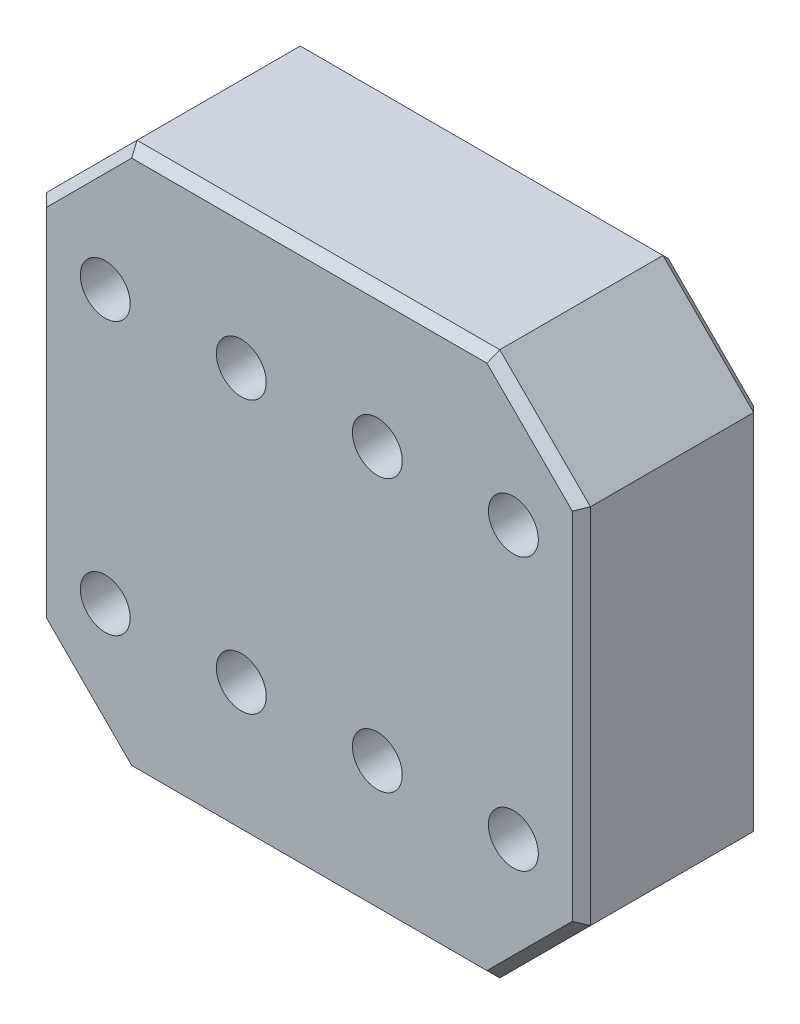
SolidWorks part; units mm, degrees
material "Q235-A"
ref_plane "前视基准面" through (0, 0, 0) normal (0, 0, 1) x (1, 0, 0)
ref_plane "上视基准面" through (0, 0, 0) normal (0, 1, 0) x (1, 0, 0)
ref_plane "右视基准面" through (0, 0, 0) normal (1, 0, 0) x (0, 0, -1)
sketch "草图1" plane through (0, 0, 0) normal (0, 0, 1) x (1, 0, 0)
  line L1 (-30, 30) -> (30, 30)
  line L2 (-30, 30) -> (-30, -30)
  line L3 (-30, -30) -> (30, -30)
  line L4 (30, 30) -> (30, -30)
  line L5 (-30, 30) -> (30, -30) construction
  line L6 (-30, -30) -> (30, 30) construction
  point P0 (0, 0)
  dimension "D1" = 60
  dimension "D2" = 60
extrude "凸台-拉伸1" add sketch "草图1" along normal blind 20
hole_wizard "打孔尺寸(%根据)内六角圆柱头螺钉的类型1" positions "草图5" profile "草图6" counterbore size "M5" standard "GB" end condition through all
sketch "草图5" plane through (0, 0, 0) normal (0, 0, -1) x (-1, 0, 0)
  line L7 (0, 0) -> (-15, 0) construction
  line L10 (-22.5, 15) -> (-7.5, 15) construction
  line L11 (-22.5, 15) -> (-22.5, -15) construction
  line L12 (-22.5, -15) -> (-7.5, -15) construction
  line L13 (-7.5, 15) -> (-7.5, -15) construction
  line L14 (-22.5, 15) -> (-7.5, -15) construction
  line L15 (-22.5, -15) -> (-7.5, 15) construction
  line L16 (0, 0) -> (15, 0) construction
  line L19 (7.5, 15) -> (22.5, 15) construction
  line L20 (7.5, 15) -> (7.5, -15) construction
  line L21 (7.5, -15) -> (22.5, -15) construction
  line L22 (22.5, 15) -> (22.5, -15) construction
  line L23 (7.5, 15) -> (22.5, -15) construction
  line L24 (7.5, -15) -> (22.5, 15) construction
  point P0 (-22.5, 15)
  point P2 (-22.5, -15)
  point P4 (-7.5, 15)
  point P6 (-7.5, -15)
  point P180 (-15, 0)
  point P191 (22.5, -15)
  point P380 (7.5, 15)
  point P381 (7.5, -15)
  point P382 (22.5, 15)
  point P385 (15, 0)
  dimension "D1" = 15
  dimension "D2" = 30
  dimension "D3" = 15
sketch "草图6" plane through (22.5, 15, 0) normal (1, 0, 0) x (0, 1, 0)
  line L0 (0, 0) -> (0, 20)
  line L1 (0, 20) -> (2.75, 20)
  line L3 (2.75, 20) -> (2.75, 14)
  line L4 (2.75, 14) -> (5, 14)
  line L5 (5, 14) -> (5, 0)
  line L7 (5, 0) -> (0, 0)
  line L11 (0, -6.35) -> (0, 107.95) construction
  dimension "通孔孔直径" = 5.5
  dimension "通孔孔深度" = 20
  dimension "柱形沉头孔直径" = 10
  dimension "柱形沉头孔深度" = 14
chamfer "倒角1" distance 10 angle 45 4 edges at (-30, -30, 10) (-30, 30, 10) (30, -30, 10) (30, 30, 10)
chamfer "倒角2" distance 1 angle 45 16 edges at (25, -25, 0) (25, 25, 0) (0, 30, 0) (-25, 25, 0) (-25, -25, 0) (0, -30, 0) (25, 25, 20) (30, 0, 20) (25, -25, 20) (0, -30, 20) (-25, -25, 20) (-30, 0, 20) (-25, 25, 20) (0, 30, 20) (30, 0, 0) (-30, 0, 0)
hole_wizard "M10 螺纹孔1" positions "草图9" profile "草图10" tap size "M10" standard "GB"
sketch "草图9" plane through (0, 0, 0) normal (0, 0, -1) x (-1, 0, 0)
  point P0 (0, 0)
sketch "草图10" plane through (0, 0, 0) normal (1, 0, 0) x (0, 1, 0)
  line L0 (0, 0) -> (0, 19.0537)
  line L1 (0, 19.0537) -> (4.25, 16.5)
  line L2 (4.25, 16.5) -> (4.25, 0)
  line L5 (4.25, 0) -> (0, 0)
  line L10 (0, 19.0537) -> (-4.25, 16.5) construction
  line L11 (0, -6.35) -> (0, 107.95) construction
  dimension "螺纹孔钻头直径" = 8.5
  dimension "螺纹孔钻头深度" = 16.5
  dimension "导头角度" = 118
cosmetic thread "孔螺蚊线1" parameters "D1"=12, "D2"=10
